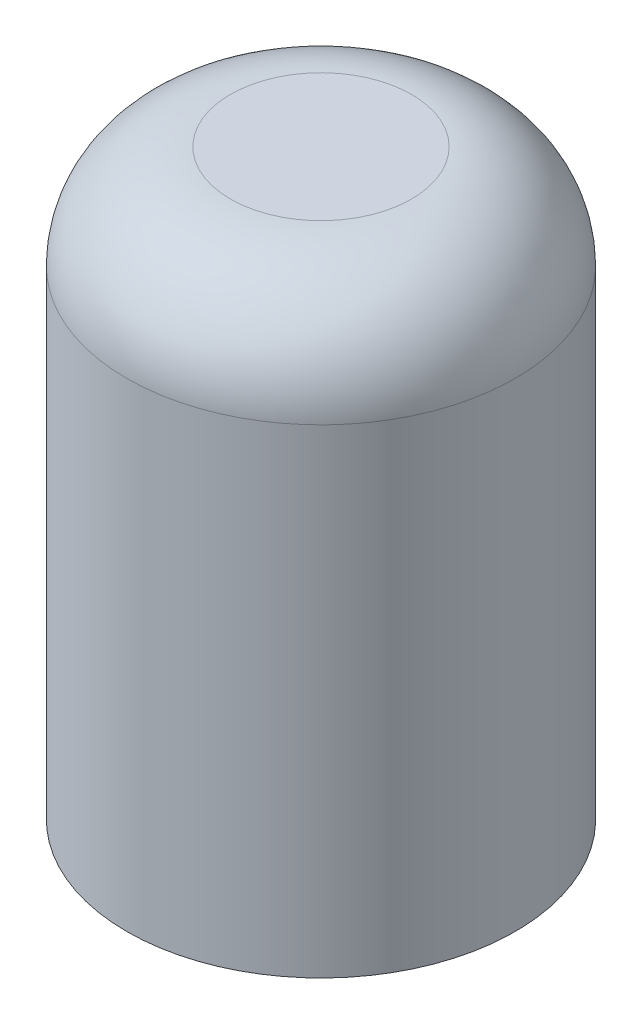
SolidWorks part; units mm, degrees
ref_plane "Front Plane" through (0, 0, 0) normal (0, 0, 1) x (1, 0, 0)
ref_plane "Top Plane" through (0, 0, 0) normal (0, 1, 0) x (1, 0, 0)
ref_plane "Right Plane" through (0, 0, 0) normal (1, 0, 0) x (0, 0, -1)
sketch "Sketch1" plane through (0, 0, 0) normal (0, 1, 0) x (1, 0, 0)
  circle A0 centre (0, 0) radius 4.7625
  dimension "D1" = 9.525
extrude "Boss-Extrude1" add sketch "Sketch1" along normal blind 14.2875
fillet "Fillet1" radius 2.54 1 edges at (0, 14.2875, 4.7625)
sketch "Sketch2" plane through (0, 0, 0) normal (0, -1, 0) x (1, 0, 0)
  circle A0 centre (0, 0) radius 1.5875
  dimension "D1" = 3.175
extrude "Cut-Extrude1" cut sketch "Sketch2" against normal blind 6.35
